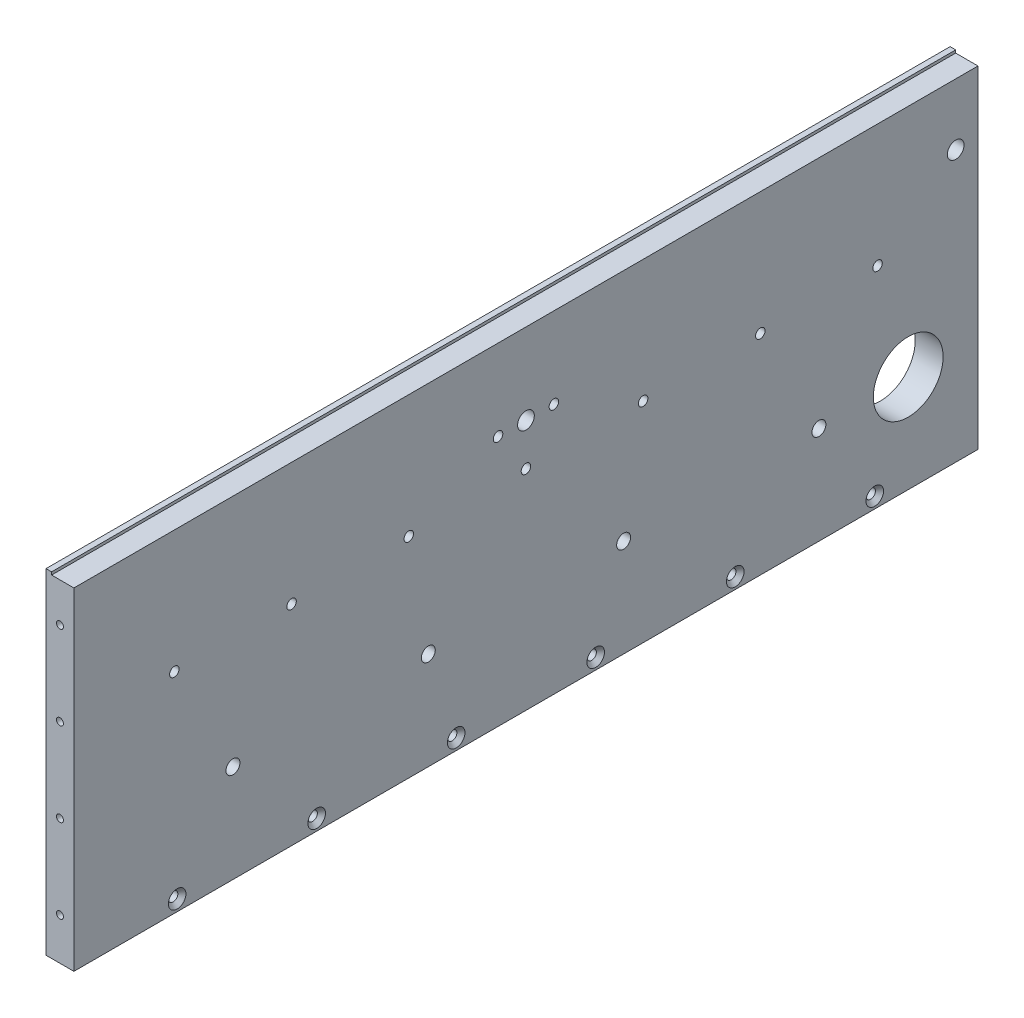
SolidWorks part; units mm, degrees
ref_plane "Front Plane" through (0, 0, 0) normal (0, 0, 1) x (1, 0, 0)
ref_plane "Top Plane" through (0, 0, 0) normal (0, 1, 0) x (1, 0, 0)
ref_plane "Right Plane" through (0, 0, 0) normal (1, 0, 0) x (0, 0, -1)
sketch "Sketch1" plane through (0, 0, 0) normal (1, 0, 0) x (0, 0, -1)
  line L1 (162, -20) -> (-162, -20)
  line L2 (162, -20) -> (162, 20)
  line L3 (162, 20) -> (-162, 20)
  line L4 (-162, -20) -> (-162, 20)
  line L5 (162, -20) -> (-162, 20) construction
  line L6 (162, 20) -> (-162, -20) construction
  point P0 (0, 0)
  dimension "D1" = 40
  dimension "D2" = 324
extrude "Boss-Extrude1" add sketch "Sketch1" along normal blind 10
sketch "Sketch2" plane through (0, 0, 0) normal (-1, 0, 0) x (0, 0, 1)
  line L0 (0, -20) -> (0, -10) construction
  line L1 (162, -20) -> (-162, -20) construction
  line L2 (-10, -20) -> (-10, -10) construction
  point P6 (0, -10)
  point P9 (-10, -10)
  dimension "D1" = 10
  dimension "D2" = 10
  dimension "D3" = 10
sketch "Sketch17" plane through (0, 0, 0) normal (-1, 0, 0) x (0, 0, 1)
  line L0 (-162, 20) -> (162, 20) construction
  line L1 (-162, -20) -> (-162, 20) construction
  circle A0 centre (-154, -3) radius 6.25
  point P0 (-154, -3)
  dimension "D3" = 12.5
  dimension "D1" = 23
  dimension "D2" = 8
hole_wizard "G1/4 Tapped Hole1" positions "3DSketch1" profile "Sketch4" tap size "G1/4" standard "DIN" end condition through all
sketch3d "3DSketch1"
  point P0 (0, -10, 0)
  point P3 (0, -3, -154)
sketch "Sketch4" plane through (0, -10, 0) normal (0, 1, 0) x (0, 0, 1)
  line L0 (0, 0) -> (0, 10)
  line L1 (0, 10) -> (3, 10)
  line L2 (3, 10) -> (3, 0)
  line L5 (3, 0) -> (0, 0)
  line L11 (0, -6.35) -> (0, 107.95) construction
  dimension "Thru Tap Drill Dia." = 6
  dimension "Thru Tap Drill Depth" = 10
cosmetic thread "Hole Thread1" parameters "D2"=13.157
cosmetic thread "Hole Thread6" parameters "D2"=13.157
hole_wizard "CSK for M3 Countersunk Flat Head1" positions "3DSketch2" profile "Sketch5" countersink size "M3" standard "BSI" end condition through all
sketch3d "3DSketch2"
  point P0 (0, -10, -10)
sketch "Sketch5" plane through (0, -10, -10) normal (0, 1, 0) x (0, 0, 1)
  line L0 (0, 0) -> (0, 10)
  line L1 (0, 10) -> (1.7, 10)
  line L2 (1.7, 10) -> (1.7, 1.45)
  line L3 (1.7, 1.45) -> (3.15, 0)
  line L5 (3.15, 0) -> (0, 0)
  line L6 (-1.7, 1.45) -> (-3.15, 0) construction
  line L11 (0, -6.35) -> (0, 107.95) construction
  dimension "Thru Hole Dia." = 3.4
  dimension "Thru Hole Depth" = 10
  dimension "Near C'Sink Dia." = 6.3
  dimension "Near C'Sink Angle" = 90
mirror "Mirror1" about plane through (0, 0, 0) normal (0, 0, 1) of "CSK for M3 Countersunk Flat Head1"
sketch "Sketch9" plane through (0, -20, 0) normal (0, -1, 0) x (1, 0, 0)
  line L4 (0, 162) -> (0, -162)
  line L5 (0, -162) -> (10, -162)
  line L6 (10, -162) -> (10, 162)
  line L7 (10, 162) -> (0, 162)
  line L8 (0, 162) -> (0, -162)
  line L9 (0, -162) -> (10, -162)
  line L10 (10, -162) -> (10, 162)
  line L11 (10, 162) -> (0, 162)
  dimension "D1" = 0
extrude "Boss-Extrude2" add sketch "Sketch9" along normal blind 80
sketch "Sketch10" plane through (10, 0, 0) normal (1, 0, 0) x (0, 0, -1)
  point P0 (-125, -96)
  point P2 (-75, -96)
  point P4 (-25, -96)
  point P6 (25, -96)
  point P8 (75, -96)
  point P10 (125, -96)
sketch "Sketch11" plane through (0, 0, 162) normal (0, 0, 1) x (1, 0, 0)
  point P0 (5, -85)
  point P2 (5, -55)
  point P4 (5, -25)
  point P6 (5, 5)
hole_wizard "CSK for M3 Countersunk Flat Head2" positions "3DSketch3" profile "Sketch12" countersink size "M3" standard "BSI"
sketch3d "3DSketch3"
  point P0 (10, -96, 125)
  point P3 (10, -96, 75)
  point P6 (10, -96, 25)
  point P9 (10, -96, -25)
  point P12 (10, -96, -75)
  point P15 (10, -96, -125)
sketch "Sketch12" plane through (10, -96, 125) normal (0, 1, 0) x (0, 0, -1)
  line L0 (0, 0) -> (0, 12.5215)
  line L1 (0, 12.5215) -> (1.7, 11.5)
  line L2 (1.7, 11.5) -> (1.7, 1.45)
  line L3 (1.7, 1.45) -> (3.15, 0)
  line L5 (3.15, 0) -> (0, 0)
  line L6 (-1.7, 1.45) -> (-3.15, 0) construction
  line L10 (0, 12.5215) -> (-1.7, 11.5) construction
  line L11 (0, -6.35) -> (0, 107.95) construction
  dimension "Hole Dia." = 3.4
  dimension "Hole Depth" = 11.5
  dimension "Near C'Sink Dia." = 6.3
  dimension "Near C'Sink Angle" = 90
  dimension "Drill Angle" = 118
hole_wizard "M3x0.5 Tapped Hole1" positions "3DSketch4" profile "Sketch13" tap size "M3x0.5" standard "BSI"
sketch3d "3DSketch4"
  point P0 (5, 5, 162)
  point P3 (5, -25, 162)
  point P6 (5, -55, 162)
  point P9 (5, -85, 162)
sketch "Sketch13" plane through (5, 5, 162) normal (1, 0, 0) x (0, -1, 0)
  line L0 (0, 0) -> (0, 12.2511)
  line L1 (0, 12.2511) -> (1.25, 11.5)
  line L2 (1.25, 11.5) -> (1.25, 0)
  line L5 (1.25, 0) -> (0, 0)
  line L10 (0, 12.2511) -> (-1.25, 11.5) construction
  line L11 (0, -6.35) -> (0, 107.95) construction
  dimension "Tap Drill Dia." = 2.5
  dimension "Tap Drill Depth" = 11.5
  dimension "Drill Angle" = 118
cosmetic thread "Hole Thread2" parameters "D1"=10, "D2"=3.5
cosmetic thread "Hole Thread3" parameters "D1"=10, "D2"=3.5
cosmetic thread "Hole Thread4" parameters "D1"=10, "D2"=3.5
cosmetic thread "Hole Thread5" parameters "D1"=10, "D2"=3.5
mirror "Mirror2" about plane through (0, 0, 0) normal (0, 0, 1) of "M3x0.5 Tapped Hole1"
sketch "Sketch14" plane through (0, 20, 0) normal (0, 1, 0) x (1, 0, 0)
  line L0 (10, -162) -> (0, -162) construction
  line L1 (10, 162) -> (2, 162)
  line L2 (10, 162) -> (10, -162)
  line L3 (10, -162) -> (2, -162)
  line L4 (2, 162) -> (2, -162)
  dimension "D1" = 8
extrude "Cut-Extrude1" cut sketch "Sketch14" against normal blind 1
sketch "Sketch15" plane through (0, 0, 0) normal (-1, 0, 0) x (0, 0, 1)
  line L0 (0, 20) -> (0, -25) construction
  line L1 (-162, 20) -> (162, 20) construction
  line L2 (0, -25) -> (-126, -25) construction
  point P7 (-126, -25)
  dimension "D1" = 45
  dimension "D2" = 126
hole_wizard "CSK for M3 Flat Head Machine Screw1" positions "3DSketch5" profile "Sketch16" countersink size "M3" standard "ANSI Metric" end condition through all
sketch3d "3DSketch5"
  point P0 (0, -25, -126)
sketch "Sketch16" plane through (0, -25, -126) normal (0, 1, 0) x (0, 0, 1)
  line L0 (0, 0) -> (0, 10)
  line L1 (0, 10) -> (1.7, 10)
  line L2 (1.7, 10) -> (1.7, 1.45)
  line L3 (1.7, 1.45) -> (3.15, 0)
  line L5 (3.15, 0) -> (0, 0)
  line L6 (-1.7, 1.45) -> (-3.15, 0) construction
  line L11 (0, -6.35) -> (0, 107.95) construction
  dimension "Thru Hole Dia." = 3.4
  dimension "Thru Hole Depth" = 10
  dimension "Near C'Sink Dia." = 6.3
  dimension "Near C'Sink Angle" = 90
pattern_linear "LPattern1" count 7 spacing 42 along (0, 0, 1) of "CSK for M3 Flat Head Machine Screw1"
sketch "Sketch18" plane through (0, 0, 0) normal (-1, 0, 0) x (0, 0, 1)
  circle A1 centre (-137, -65) radius 12.5
  circle A2 centre (-137, -65) radius 12.5
  circle A3 centre (-105, -65) radius 2.5
  circle A4 centre (-105, -65) radius 2.5
  circle A5 centre (-35, -65) radius 2.5
  circle A6 centre (-35, -65) radius 2.5
  circle A7 centre (35, -65) radius 2.5
  circle A8 centre (35, -65) radius 2.5
  circle A9 centre (105, -65) radius 2.5
  circle A10 centre (105, -65) radius 2.5
  dimension "D1" = 0
  dimension "D2" = 0
  dimension "D3" = 0
  dimension "D4" = 0
  dimension "D5" = 0
extrude "mod_cut" cut sketch "Sketch18" against normal through all
